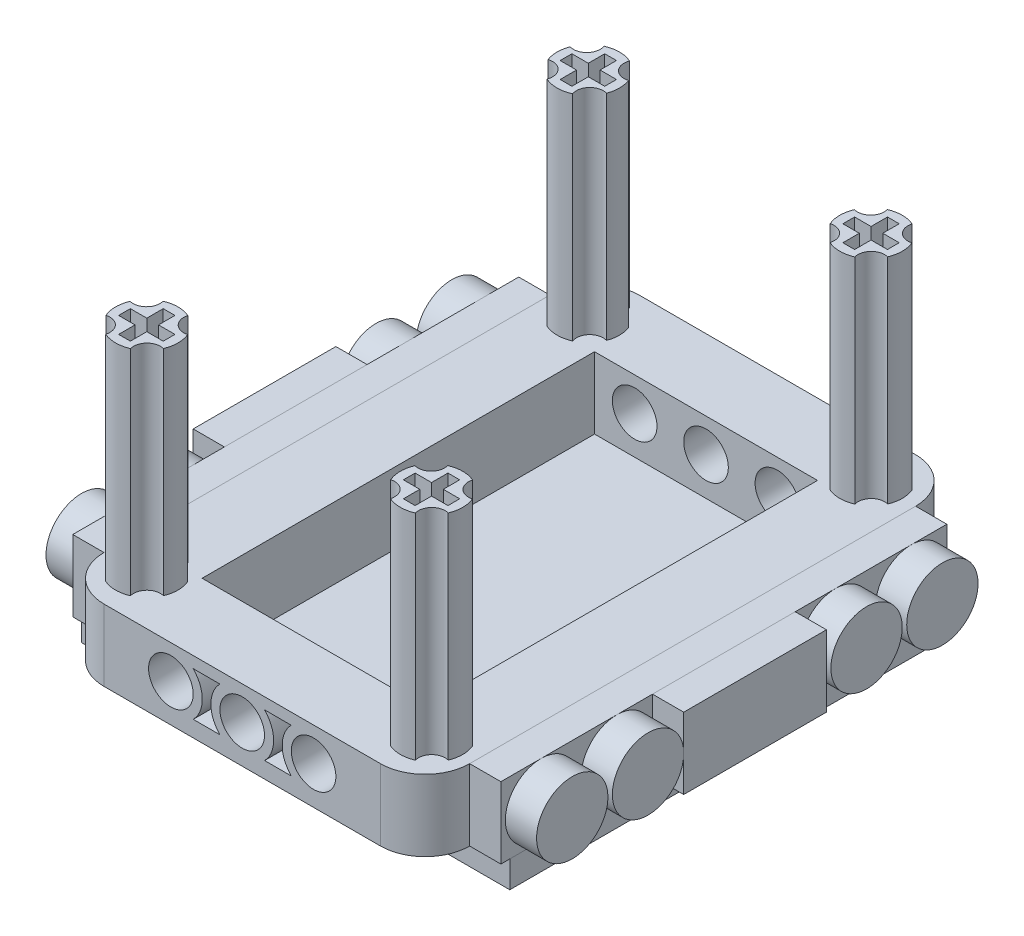
SolidWorks part; units mm, degrees
ref_plane "Front Plane" through (0, 0, 0) normal (0, 0, 1) x (1, 0, 0)
ref_plane "Top Plane" through (0, 0, 0) normal (0, 1, 0) x (1, 0, 0)
ref_plane "Right Plane" through (0, 0, 0) normal (1, 0, 0) x (0, 0, -1)
sketch "Sketch1" plane through (0, 0, 0) normal (0, 1, 0) x (1, 0, 0)
  line L1 (24, 24) -> (-24, 24)
  line L2 (24, 24) -> (24, -24)
  line L3 (24, -24) -> (-24, -24)
  line L4 (-24, 24) -> (-24, -24)
  point P0 (0, 0)
  dimension "D1" = 48
  dimension "D2" = 48
  dimension "D3" = 24
  dimension "D4" = 24
extrude "Boss-Extrude1" add sketch "Sketch1" along normal blind 3
sketch "Sketch2" plane through (0, 3, 0) normal (0, 1, 0) x (1, 0, 0)
  line L0 (-12.5, 22) -> (-12.5, -22)
  line L1 (15.5, 30) -> (-15.5, 30)
  line L2 (20.5, 25) -> (20.5, -25)
  line L3 (15.5, -30) -> (-15.5, -30)
  line L4 (-20.5, 25) -> (-20.5, -25)
  line L5 (20.5, 30) -> (-20.5, -30) construction
  line L6 (20.5, -30) -> (-20.5, 30) construction
  line L7 (12.5, -22) -> (-12.5, -22)
  line L8 (12.5, 22) -> (12.5, -22)
  line L9 (12.5, 22) -> (-12.5, 22)
  line L10 (20.5, -30) -> (-20.5, -30) construction
  line L11 (-20.5, 30) -> (-20.5, -30) construction
  line L12 (20.5, 30) -> (20.5, -30) construction
  line L13 (20.5, 30) -> (-20.5, 30) construction
  arc A0 (-15.5, -30) -> (-20.5, -25) centre (-15.5, -25) cw
  arc A1 (20.5, -25) -> (15.5, -30) centre (15.5, -25) cw
  arc A2 (15.5, 30) -> (20.5, 25) centre (15.5, 25) cw
  arc A3 (-15.5, 30) -> (-20.5, 25) centre (-15.5, 25) ccw
  point P0 (0, 0)
  dimension "D4" = 5
  dimension "D1" = 41
  dimension "D2" = 60
  dimension "D3" = 8
extrude "Boss-Extrude2" add sketch "Sketch2" along normal blind 8
sketch "Sketch4" plane through (0, 11, 0) normal (0, 1, 0) x (1, 0, 0)
  line L5 (14.8412, 25.6588) -> (13, 25.6588)
  line L6 (16.1588, 22.5) -> (14.8412, 22.5)
  line L11 (16.1588, 22.5) -> (16.1588, 24.3412)
  line L12 (16.1588, 27.5) -> (14.8412, 27.5)
  line L16 (14.8412, 22.5) -> (14.8412, 24.3412)
  line L17 (18, 24.3412) -> (16.1588, 24.3412)
  line L18 (18, 24.3412) -> (18, 25.6588)
  line L19 (18, 25.6588) -> (16.1588, 25.6588)
  line L20 (13, 24.3412) -> (13, 25.6588)
  line L21 (14.8412, 25.6588) -> (14.8412, 27.5)
  line L22 (16.1588, 25.6588) -> (16.1588, 27.5)
  line L23 (14.8412, 24.3412) -> (13, 24.3412)
  line L24 (15.0663, -23.8412) -> (13.2251, -23.8412)
  line L25 (16.3839, -27) -> (15.0663, -27)
  line L26 (16.3839, -27) -> (16.3839, -25.1588)
  line L27 (16.3839, -22) -> (15.0663, -22)
  line L28 (15.0663, -27) -> (15.0663, -25.1588)
  line L29 (18.2251, -25.1588) -> (16.3839, -25.1588)
  line L30 (18.2251, -25.1588) -> (18.2251, -23.8412)
  line L31 (18.2251, -23.8412) -> (16.3839, -23.8412)
  line L32 (13.2251, -25.1588) -> (13.2251, -23.8412)
  line L33 (15.0663, -23.8412) -> (15.0663, -22)
  line L34 (16.3839, -23.8412) -> (16.3839, -22)
  line L35 (15.0663, -25.1588) -> (13.2251, -25.1588)
  line L36 (-16.8588, -23.8412) -> (-18.7, -23.8412)
  line L37 (-15.5412, -27) -> (-16.8588, -27)
  line L38 (-15.5412, -27) -> (-15.5412, -25.1588)
  line L39 (-15.5412, -22) -> (-16.8588, -22)
  line L40 (-16.8588, -27) -> (-16.8588, -25.1588)
  line L41 (-13.7, -25.1588) -> (-15.5412, -25.1588)
  line L42 (-13.7, -25.1588) -> (-13.7, -23.8412)
  line L43 (-13.7, -23.8412) -> (-15.5412, -23.8412)
  line L44 (-18.7, -25.1588) -> (-18.7, -23.8412)
  line L45 (-16.8588, -23.8412) -> (-16.8588, -22)
  line L46 (-15.5412, -23.8412) -> (-15.5412, -22)
  line L47 (-16.8588, -25.1588) -> (-18.7, -25.1588)
  line L48 (-16.8588, 25.6588) -> (-18.7, 25.6588)
  line L49 (-15.5412, 22.5) -> (-16.8588, 22.5)
  line L50 (-15.5412, 22.5) -> (-15.5412, 24.3412)
  line L51 (-15.5412, 27.5) -> (-16.8588, 27.5)
  line L52 (-16.8588, 22.5) -> (-16.8588, 24.3412)
  line L53 (-13.7, 24.3412) -> (-15.5412, 24.3412)
  line L54 (-13.7, 24.3412) -> (-13.7, 25.6588)
  line L55 (-13.7, 25.6588) -> (-15.5412, 25.6588)
  line L56 (-18.7, 24.3412) -> (-18.7, 25.6588)
  line L57 (-16.8588, 25.6588) -> (-16.8588, 27.5)
  line L58 (-15.5412, 25.6588) -> (-15.5412, 27.5)
  line L59 (-16.8588, 24.3412) -> (-18.7, 24.3412)
  arc A8 (12.2739, 26.3572) -> (12.2739, 23.6428) centre (15.5, 25) ccw
  arc A9 (12.2739, 26.3572) -> (14.1068, 28.2108) centre (12.6625, 27.806) ccw
  arc A10 (16.8932, 28.2108) -> (18.7261, 26.3572) centre (18.3375, 27.806) ccw
  arc A11 (16.8932, 21.7892) -> (18.7261, 23.6428) centre (18.3375, 22.194) cw
  arc A12 (12.2739, 23.6428) -> (14.1068, 21.7892) centre (12.6625, 22.194) cw
  arc A13 (16.8932, 28.2108) -> (14.1068, 28.2108) centre (15.5, 25) ccw
  arc A14 (18.7261, 23.6428) -> (18.7261, 26.3572) centre (15.5, 25) ccw
  arc A15 (14.1068, 21.7892) -> (16.8932, 21.7892) centre (15.5, 25) ccw
  arc A16 (12.499, -23.1428) -> (12.499, -25.8572) centre (15.7251, -24.5) ccw
  arc A17 (12.499, -23.1428) -> (14.3319, -21.2892) centre (12.8876, -21.694) ccw
  arc A18 (17.1183, -21.2892) -> (18.9512, -23.1428) centre (18.5626, -21.694) ccw
  arc A19 (17.1183, -27.7108) -> (18.9512, -25.8572) centre (18.5626, -27.306) cw
  arc A20 (12.499, -25.8572) -> (14.3319, -27.7108) centre (12.8876, -27.306) cw
  arc A21 (17.1183, -21.2892) -> (14.3319, -21.2892) centre (15.7251, -24.5) ccw
  arc A22 (18.9512, -25.8572) -> (18.9512, -23.1428) centre (15.7251, -24.5) ccw
  arc A23 (14.3319, -27.7108) -> (17.1183, -27.7108) centre (15.7251, -24.5) ccw
  arc A24 (-19.4261, -23.1428) -> (-19.4261, -25.8572) centre (-16.2, -24.5) ccw
  arc A25 (-19.4261, -23.1428) -> (-17.5932, -21.2892) centre (-19.0375, -21.694) ccw
  arc A26 (-14.8068, -21.2892) -> (-12.9739, -23.1428) centre (-13.3625, -21.694) ccw
  arc A27 (-14.8068, -27.7108) -> (-12.9739, -25.8572) centre (-13.3625, -27.306) cw
  arc A28 (-19.4261, -25.8572) -> (-17.5932, -27.7108) centre (-19.0375, -27.306) cw
  arc A29 (-14.8068, -21.2892) -> (-17.5932, -21.2892) centre (-16.2, -24.5) ccw
  arc A30 (-12.9739, -25.8572) -> (-12.9739, -23.1428) centre (-16.2, -24.5) ccw
  arc A31 (-17.5932, -27.7108) -> (-14.8068, -27.7108) centre (-16.2, -24.5) ccw
  arc A32 (-19.4748, 26.2353) -> (-19.4748, 23.7647) centre (-16.2, 25) ccw
  arc A33 (-19.4748, 26.2353) -> (-17.6319, 28.1937) centre (-19.0375, 27.6701) ccw
  arc A34 (-14.7681, 28.1937) -> (-12.9252, 26.2353) centre (-13.3625, 27.6701) ccw
  arc A35 (-14.7681, 21.8063) -> (-12.9252, 23.7647) centre (-13.3625, 22.3299) cw
  arc A36 (-19.4748, 23.7647) -> (-17.6319, 21.8063) centre (-19.0375, 22.3299) cw
  arc A37 (-14.7681, 28.1937) -> (-17.6319, 28.1937) centre (-16.2, 25) ccw
  arc A38 (-12.9252, 23.7647) -> (-12.9252, 26.2353) centre (-16.2, 25) ccw
  arc A39 (-17.6319, 21.8063) -> (-14.7681, 21.8063) centre (-16.2, 25) ccw
  point P21 (0, 0)
  point P24 (0, 0)
  point P27 (-18.7, 25)
  point P28 (-13.7, 25)
  point P29 (-16.2, 27.5)
  point P30 (-16.2, 22.5)
  point P31 (0, 0)
  point P32 (0, 0)
  point P33 (0, 0)
  point P34 (0, 0)
  point P35 (0, 0)
  point P36 (0, 0)
  point P37 (0, 0)
  point P81 (13, 25)
  point P82 (18, 25)
  point P83 (15.5, 27.5)
  point P84 (15.5, 22.5)
  point P113 (13.2251, -24.5)
  point P114 (18.2251, -24.5)
  point P115 (15.7251, -22)
  point P116 (15.7251, -27)
  point P143 (-18.7, -24.5)
  point P144 (-13.7, -24.5)
  point P145 (-16.2, -22)
  point P146 (-16.2, -27)
  dimension "D4" = 5
  dimension "D5" = 5
  dimension "D8" = 7
  dimension "D11" = 1.5
  dimension "D14" = 7
  dimension "D17" = 1.5
  dimension "D20" = 7
  dimension "D23" = 1.5
  dimension "D3" = 7
  dimension "D6" = 1.5
  dimension "D7" = 1.8412
  dimension "D9" = 5
  dimension "D10" = 5
  dimension "D12" = 1.8412
  dimension "D13" = 2.5
  dimension "D15" = 5
  dimension "D16" = 5
  dimension "D18" = 1.8412
  dimension "D19" = 2.5
  dimension "D21" = 5
  dimension "D22" = 5
  dimension "D24" = 1.8412
  dimension "D25" = 2.5
  dimension "D26" = 2.5
  dimension "D27" = 49.5
  dimension "D28" = 31.9251
  dimension "D29" = 4.3
extrude "Boss-Extrude4" add sketch "Sketch4" along normal blind 24
sketch "Sketch5" plane through (0, 0, 30) normal (0, 0, 1) x (1, 0, 0)
  line L0 (0, 7.2486) -> (-8, 7.2486) construction
  line L1 (0, 7.2486) -> (8, 7.2486) construction
  circle A0 centre (0, 7.2486) radius 2.5
  circle A1 centre (-8, 7.2486) radius 2.5
  circle A2 centre (8, 7.2486) radius 2.5
  dimension "D1" = 2
  dimension "D3" = 5
  dimension "D2" = 8
  dimension "D5" = 8
  dimension "D4" = 2
sketch "Sketch6" plane through (0, 0, 30) normal (0, 0, 1) x (1, 0, 0)
  line L0 (-2.4899, 9.7486) -> (-5.4899, 9.7486)
  line L1 (5.5129, 9.7486) -> (2.5129, 9.7486)
  line L2 (-5.5, 4.8272) -> (-2.5, 4.8272)
  line L3 (2.5029, 4.8272) -> (5.5029, 4.8272)
  arc A4 (-5.4899, 9.7486) -> (-5.5, 4.8272) centre (-7.9557, 7.2929) cw
  arc A5 (-2.4899, 9.7486) -> (-2.5, 4.8272) centre (-0.0342, 7.2829) ccw
  arc A6 (2.5129, 9.7486) -> (2.5029, 4.8272) centre (0.0472, 7.2929) cw
  arc A7 (5.5129, 9.7486) -> (5.5029, 4.8272) centre (7.9687, 7.2829) ccw
  dimension "D2" = 3
  dimension "D1" = 3
sketch "Sketch11" plane through (0, 0, -30) normal (0, 0, -1) x (-1, 0, 0)
  line L0 (-2.5, 9.7278) -> (-5.5, 9.7278)
  line L1 (5.5029, 9.7278) -> (2.5029, 9.7278)
  line L2 (-5.51, 4.8063) -> (-2.51, 4.8063)
  line L3 (2.4928, 4.8063) -> (5.4928, 4.8063)
  arc A0 (-5.5, 9.7278) -> (-5.51, 4.8063) centre (-7.9658, 7.2721) cw
  arc A1 (-2.5, 9.7278) -> (-2.51, 4.8063) centre (-0.0443, 7.262) ccw
  arc A2 (2.5029, 9.7278) -> (2.4928, 4.8063) centre (0.0371, 7.2721) cw
  arc A3 (5.5029, 9.7278) -> (5.4928, 4.8063) centre (7.9586, 7.262) ccw
  point P7 (-4.01, 4.8063)
  point P13 (3.9928, 4.8063)
  point P14 (0, 0)
  point P15 (0, 0)
  dimension "D1" = 3
  dimension "D2" = 3
sketch "Sketch23" plane through (-20.5, 0, 0) normal (-1, 0, 0) x (0, 0, 1)
  line L1 (-25, 11) -> (25, 11)
  line L2 (-25, 11) -> (-25, 3)
  line L3 (-25, 3) -> (25, 3)
  line L4 (25, 11) -> (25, 3)
extrude "Boss-Extrude5" add sketch "Sketch23" along normal blind 3.5 separate body
sketch "Sketch24" plane through (-24, 0, 0) normal (-1, 0, 0) x (0, 0, 1)
  line L0 (-24, 3) -> (24, 3) construction
  line L1 (8, 11) -> (-8, 11)
  line L2 (8, 11) -> (8, 3)
  line L3 (8, 3) -> (-8, 3)
  line L4 (-8, 11) -> (-8, 3)
  line L5 (8, 11) -> (-8, 3) construction
  line L6 (8, 3) -> (-8, 11) construction
  point P0 (0, 7)
  point P7 (0, 0)
  dimension "D1" = 16
  dimension "D2" = 8
extrude "Boss-Extrude6" add sketch "Sketch24" along normal blind 3.5 separate body
sketch "Sketch25" plane through (-24, 0, 0) normal (-1, 0, 0) x (0, 0, 1)
  line L0 (-25, 3) -> (25, 3) construction
  line L1 (-25, 11) -> (-25, 3) construction
  line L2 (-24, 3) -> (24, 3) construction
  line L3 (8, 3) -> (8, 11) construction
  circle A0 centre (20.5, 7) radius 4
  circle A1 centre (12, 7) radius 4
  circle A2 centre (-12.5, 7) radius 4
  circle A3 centre (-21, 7) radius 4
  point P8 (-10.4784, 6.7761)
  dimension "D3" = 8
  dimension "D4" = 8
  dimension "D6" = 8
  dimension "D1" = 8.5
  dimension "D2" = 8.5
  dimension "D5" = 2
extrude "Boss-Extrude7" add sketch "Sketch25" along normal blind 3.5 separate body
mirror "Mirror10" about plane through (0, 0, 0) normal (1, 0, 0) of bodies 127 128
mirror "Mirror11" about plane through (0, 0, 0) normal (1, 0, 0) of bodies 130 129 131 132
extrude "Cut-Extrude1" cut sketch "Sketch5" against normal through all both and the other way through all contours A1
pattern_linear "LPattern1" count 3 spacing 8 along (1, 0, 0) of "Cut-Extrude1"
extrude "Cut-Extrude2" cut sketch "Sketch11" against normal blind 2 contours A2 L3 A3 L1
pattern_linear "LPattern2" count 2 spacing 8 along (1, 0, 0) of "Cut-Extrude2"
mirror "Mirror12" about plane through (0, 0, 0) normal (0, 0, 1) of "Cut-Extrude2"
pattern_linear "LPattern3" count 2 spacing 8 along (1, 0, 0) of "Mirror12"
